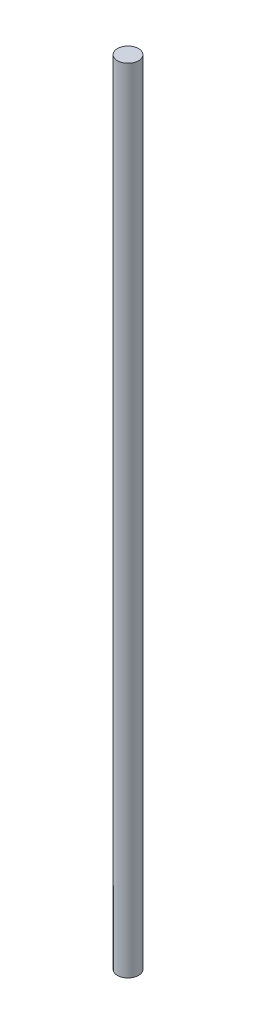
SolidWorks part; units mm, degrees
ref_plane "Alzado" through (0, 0, 0) normal (0, 0, 1) x (1, 0, 0)
ref_plane "Planta" through (0, 0, 0) normal (0, 1, 0) x (1, 0, 0)
ref_plane "Vista lateral" through (0, 0, 0) normal (1, 0, 0) x (0, 0, -1)
sketch "Croquis1" plane through (0, 0, 0) normal (0, 1, 0) x (1, 0, 0)
  circle A0 centre (0, 0) radius 1.6
  dimension "D1" = 3.2
extrude "Saliente-Extruir1" add sketch "Croquis1" along normal blind 120
